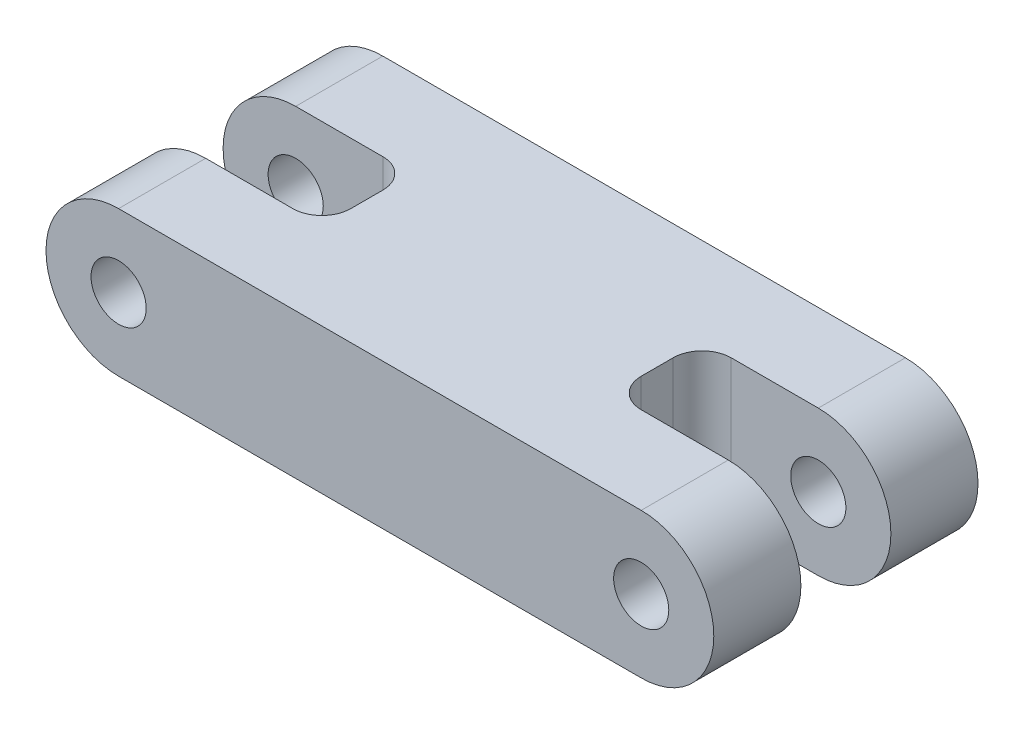
SolidWorks part; units mm, degrees
ref_plane "正面" through (0, 0, 0) normal (0, 0, 1) x (1, 0, 0)
ref_plane "平面" through (0, 0, 0) normal (0, 1, 0) x (1, 0, 0)
ref_plane "右側面" through (0, 0, 0) normal (1, 0, 0) x (0, 0, -1)
sketch "ｽｹｯﾁ1" plane through (0, 0, 0) normal (0, 0, 1) x (1, 0, 0)
  line L0 (0, 5) -> (-36, 5)
  line L1 (0, -5) -> (-36, -5)
  arc A0 (0, 5) -> (0, -5) centre (0, 0) cw
  arc A1 (-36, 5) -> (-36, -5) centre (-36, 0) ccw
  dimension "D1" = 5
  dimension "D2" = 5
  dimension "D3" = 36
extrude "ﾎﾞｽ - 押し出し1" add sketch "ｽｹｯﾁ1" along normal blind 6 from offset 9.1 offset against normal yes
sketch "ｽｹｯﾁ5" plane through (0, 0, -3.1) normal (0, 0, 1) x (1, 0, 0)
  circle A0 centre (-36, 0) radius 1.9
  arc A1 (-36, 5) -> (-36, -5) centre (-36, 0) ccw construction
  dimension "D1" = 3.8
extrude "ｶｯﾄ - 押し出し5" cut sketch "ｽｹｯﾁ5" against normal through all
sketch "ｽｹｯﾁ6" plane through (0, 0, -3.1) normal (0, 0, 1) x (1, 0, 0)
  circle A0 centre (0, 0) radius 1.9
  dimension "D1" = 3.8
extrude "ｶｯﾄ - 押し出し6" cut sketch "ｽｹｯﾁ6" against normal blind 10
sketch "ｽｹｯﾁ7" plane through (0, 0, -3.1) normal (0, 0, 1) x (1, 0, 0)
  line L0 (0, 5) -> (-36, 5) construction
  line L1 (-8, 5) -> (-28, 5)
  line L2 (-8, 5) -> (-8, -5)
  line L3 (-8, -5) -> (-28, -5)
  line L4 (-28, 5) -> (-28, -5)
  line L5 (-36, -5) -> (0, -5) construction
  circle A1 centre (0, 0) radius 1.9 construction
  circle A2 centre (-36, 0) radius 1.9 construction
  dimension "D1" = 8
  dimension "D2" = 8
extrude "ﾎﾞｽ - 押し出し2" add sketch "ｽｹｯﾁ7" along normal up to surface (3.1 mm away) up to plane "正面"
mirror "ﾐﾗｰ3" about plane through (0, 0, 0) normal (0, 0, 1) of "ｶｯﾄ - 押し出し5", "ｶｯﾄ - 押し出し6", "ﾎﾞｽ - 押し出し1", "ﾎﾞｽ - 押し出し2"
fillet "ﾌｨﾚｯﾄ1" radius 2 4 edges at (-28, 0, 3.1) (-28, 0, -3.1) (-8, 0, 3.1) (-8, 0, -3.1)
